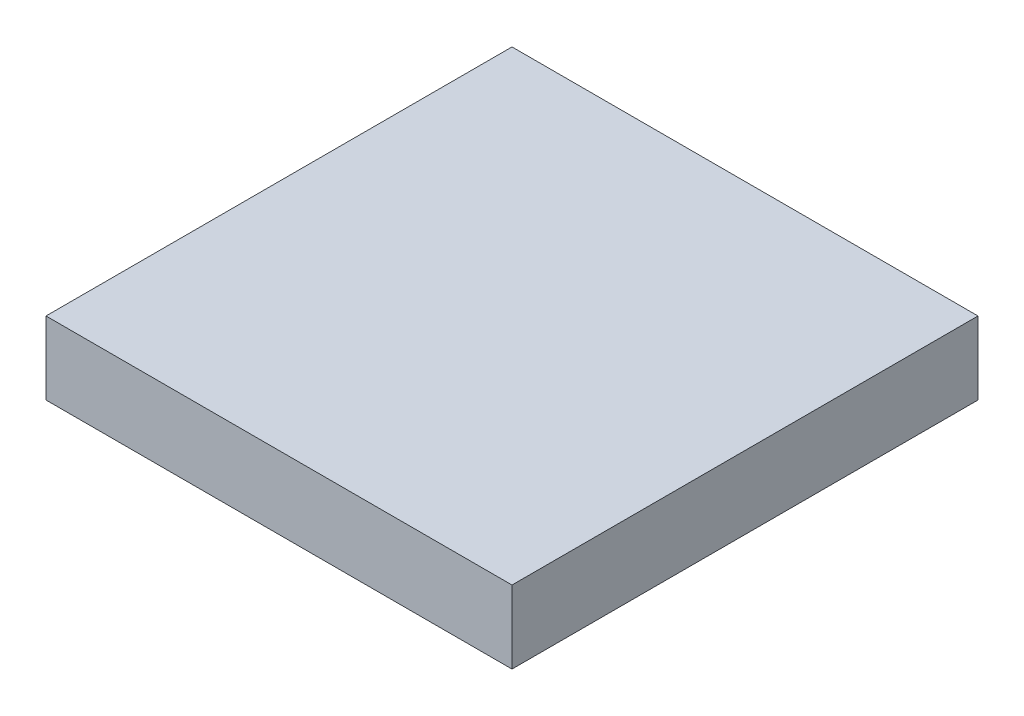
SolidWorks part; units mm, degrees
ref_plane "Plano frontal" through (0, 0, 0) normal (0, 0, 1) x (1, 0, 0)
ref_plane "Plano superior" through (0, 0, 0) normal (0, 1, 0) x (1, 0, 0)
ref_plane "Plano direito" through (0, 0, 0) normal (1, 0, 0) x (0, 0, -1)
sketch "Esboço1" plane through (0, 15, 0) normal (0, 1, 0) x (1, 0, 0)
  line L0 (-32, -0.5) -> (32, -0.5)
  line L1 (32, -0.5) -> (32, -64.5)
  line L2 (32, -64.5) -> (-32, -64.5)
  line L3 (-32, -64.5) -> (-32, -0.5)
extrude "Ressalto-extrusão1" add sketch "Esboço1" along normal blind 10
